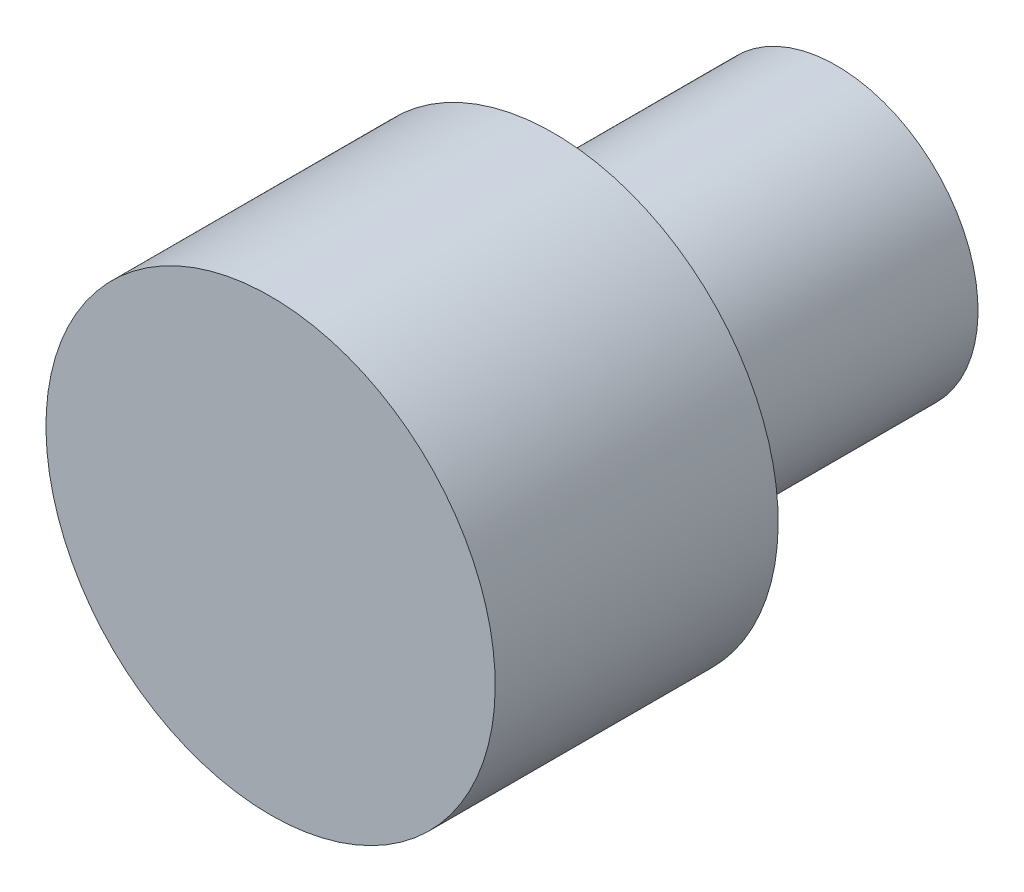
SolidWorks part; units mm, degrees
ref_plane "前视基准面" through (0, 0, 0) normal (0, 0, 1) x (1, 0, 0)
ref_plane "上视基准面" through (0, 0, 0) normal (0, 1, 0) x (1, 0, 0)
ref_plane "右视基准面" through (0, 0, 0) normal (1, 0, 0) x (0, 0, -1)
sketch "草图1" plane through (0, 0, 0) normal (1, 0, 0) x (0, 0, -1)
  line L0 (0, 0) -> (144.8481, 0) construction
  line L1 (0, 0) -> (0, 6.35)
  line L2 (0, 6.35) -> (8, 6.35)
  line L3 (8, 6.35) -> (8, 4)
  line L4 (8, 4) -> (16, 4)
  line L5 (16, 4) -> (16, 0)
  line L6 (0, 0) -> (16, 0)
  dimension "D1" = 6.35
  dimension "D2" = 8
  dimension "D3" = 8
  dimension "D4" = 8
revolve "旋转1" add sketch "草图1" angle 360 about L0
